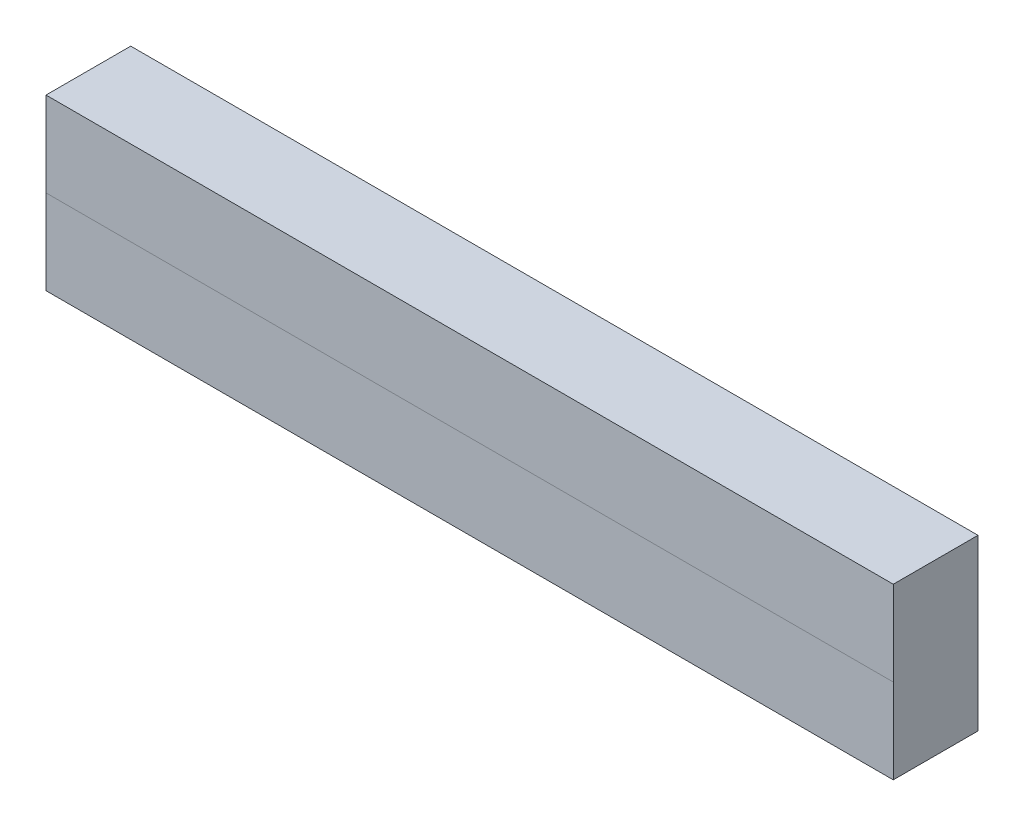
SolidWorks part; units mm, degrees
ref_plane "Спереди" through (0, 0, 0) normal (0, 0, 1) x (1, 0, 0)
ref_plane "Сверху" through (0, 0, 0) normal (0, 1, 0) x (1, 0, 0)
ref_plane "Справа" through (0, 0, 0) normal (1, 0, 0) x (0, 0, -1)
sketch "Эскиз1" plane through (0, 0, 0) normal (1, 0, 0) x (0, 0, -1)
  line L1 (5, -10) -> (-5, -10)
  line L2 (5, -10) -> (5, 10)
  line L3 (5, 10) -> (-5, 10)
  line L4 (-5, -10) -> (-5, 10)
  line L5 (5, -10) -> (-5, 10) construction
  line L6 (5, 10) -> (-5, -10) construction
  point P0 (0, 0)
  dimension "D1" = 10
  dimension "D2" = 20
extrude "Бобышка-Вытянуть1" add sketch "Эскиз1" along normal blind 100
sketch "Эскиз2" plane through (0, 0, 5) normal (0, 0, 1) x (1, 0, 0)
  line L0 (0, 0) -> (100, 0)
  line L1 (100, 10) -> (100, -10) construction
split line "Разделяющая линия1"
